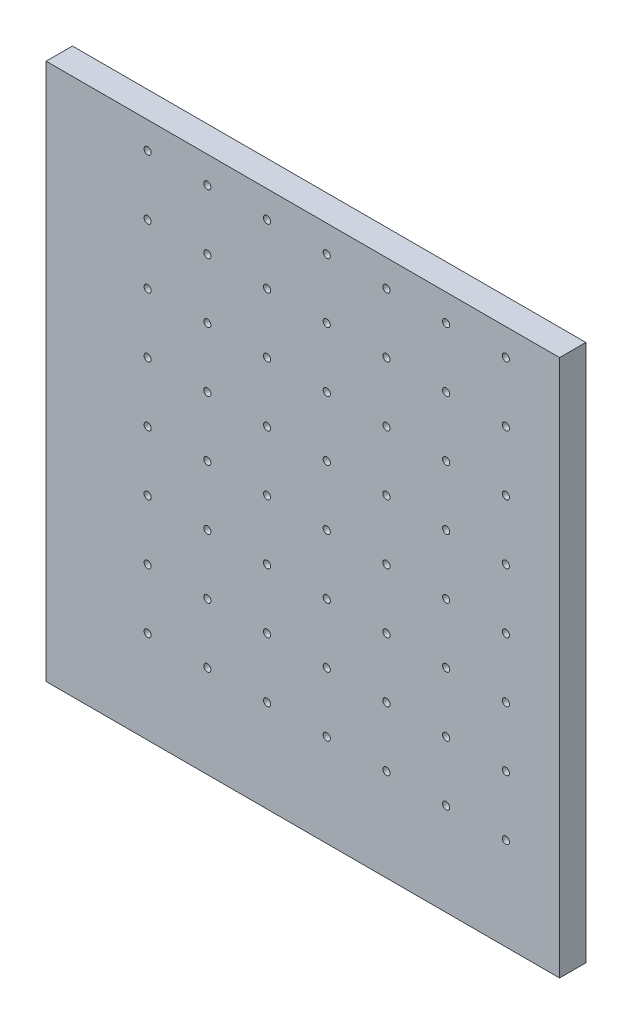
SolidWorks part; units mm, degrees
ref_plane "Front" through (0, 0, 0) normal (0, 0, 1) x (1, 0, 0)
ref_plane "Top" through (0, 0, 0) normal (0, 1, 0) x (1, 0, 0)
ref_plane "Right" through (0, 0, 0) normal (1, 0, 0) x (0, 0, -1)
sketch "Esquisse1" plane through (0, 0, 0) normal (0, 0, 1) x (1, 0, 0)
  line L1 (0, 0) -> (430, 0)
  line L2 (0, 0) -> (0, 450)
  line L3 (0, 450) -> (430, 450)
  line L4 (430, 0) -> (430, 450)
  dimension "D1" = 430
  dimension "D2" = 450
extrude "Boss.-Extru.1" add sketch "Esquisse1" along normal blind 22
sketch "Esquisse2" plane through (0, 0, 22) normal (0, 0, 1) x (1, 0, 0)
  line L0 (235, 115) -> (235, 25) construction
  line L1 (110, 390) -> (360, 390)
  line L2 (110, 390) -> (110, 115)
  line L3 (110, 115) -> (360, 115)
  line L4 (360, 390) -> (360, 115)
  line L5 (0, 0) -> (430, 0) construction
  line L6 (0, 450) -> (0, 0) construction
  line L7 (430, 450) -> (0, 450) construction
  line L8 (430, 0) -> (430, 450) construction
  dimension "D1" = 115
  dimension "D2" = 110
  dimension "D3" = 60
  dimension "D4" = 70
extrude "Enlèv. mat.-Extru.1" cut sketch "Esquisse2" along normal blind 1 from vertex at -22 starting at point (0, 450, 0)
sketch "Esquisse3" plane through (0, 0, 0) normal (0, 0, -1) x (-1, 0, 0)
  line L3 (-360, 252.5) -> (-110, 252.5) construction
  line L4 (-360, 115) -> (-360, 390) construction
  line L5 (-110, 390) -> (-110, 115) construction
  line L6 (-310, 252.5) -> (-310, 281.622) construction
  line L7 (-160, 252.5) -> (-160, 281.622) construction
  line L8 (-235, 302.5) -> (-255.5628, 302.5) construction
  line L9 (-160, 352.5) -> (-160, 323.378) construction
  line L10 (-310, 352.5) -> (-310, 323.378) construction
  line L11 (-360, 352.5) -> (-110, 352.5) construction
  line L16 (-314.1888, 402.5) -> (-265.4372, 402.5) construction
  line L17 (-430, 0) -> (-430, 450) construction
  line L18 (0, 0) -> (-430, 0) construction
  circle A0 centre (-385, 277.5) radius 3
  circle A1 centre (-335, 277.5) radius 3
  circle A2 centre (-135, 77.5) radius 3
  circle A3 centre (-85, 77.5) radius 3
  circle A4 centre (-185, 77.5) radius 3
  circle A5 centre (-285, 77.5) radius 3
  circle A6 centre (-285, 277.5) radius 3
  circle A7 centre (-235, 277.5) radius 3
  circle A8 centre (-185, 277.5) radius 3
  circle A9 centre (-235, 77.5) radius 3
  circle A10 centre (-385, 77.5) radius 3
  circle A11 centre (-335, 77.5) radius 3
  circle A12 centre (-135, 277.5) radius 3
  circle A13 centre (-85, 277.5) radius 3
  circle A14 centre (-85, 327.5) radius 3
  circle A15 centre (-135, 327.5) radius 3
  circle A16 centre (-135, 377.5) radius 3
  circle A17 centre (-85, 377.5) radius 3
  circle A18 centre (-185, 377.5) radius 3
  circle A19 centre (-185, 327.5) radius 3
  circle A20 centre (-235, 327.5) radius 3
  circle A21 centre (-285, 327.5) radius 3
  circle A22 centre (-285, 377.5) radius 3
  circle A23 centre (-235, 377.5) radius 3
  circle A24 centre (-385, 377.5) radius 3
  circle A25 centre (-335, 377.5) radius 3
  circle A26 centre (-335, 327.5) radius 3
  circle A27 centre (-385, 327.5) radius 3
  circle A28 centre (-385, 177.5) radius 3
  circle A29 centre (-335, 177.5) radius 3
  circle A30 centre (-335, 127.5) radius 3
  circle A31 centre (-385, 127.5) radius 3
  circle A32 centre (-235, 127.5) radius 3
  circle A33 centre (-285, 127.5) radius 3
  circle A34 centre (-285, 177.5) radius 3
  circle A35 centre (-235, 177.5) radius 3
  circle A36 centre (-185, 177.5) radius 3
  circle A37 centre (-185, 127.5) radius 3
  circle A38 centre (-85, 127.5) radius 3
  circle A39 centre (-135, 127.5) radius 3
  circle A40 centre (-135, 177.5) radius 3
  circle A41 centre (-85, 177.5) radius 3
  circle A42 centre (-85, 227.5) radius 3
  circle A43 centre (-135, 227.5) radius 3
  circle A44 centre (-185, 227.5) radius 3
  circle A45 centre (-235, 227.5) radius 3
  circle A46 centre (-285, 227.5) radius 3
  circle A47 centre (-335, 227.5) radius 3
  circle A48 centre (-385, 227.5) radius 3
  circle A49 centre (-335, 427.5) radius 3
  circle A50 centre (-385, 427.5) radius 3
  circle A51 centre (-235, 427.5) radius 3
  circle A52 centre (-285, 427.5) radius 3
  circle A53 centre (-185, 427.5) radius 3
  circle A54 centre (-85, 427.5) radius 3
  circle A55 centre (-135, 427.5) radius 3
  dimension "D1" = 6
  dimension "D3" = 25
  dimension "D4" = 50
  dimension "D5" = 50
  dimension "D6" = 50
  dimension "D9" = 175
  dimension "D11" = 225
  dimension "D12" = 275
  dimension "D13" = 25
  dimension "D15" = 125
extrude "Enlèv. mat.-Extru.2" cut sketch "Esquisse3" against normal through all
